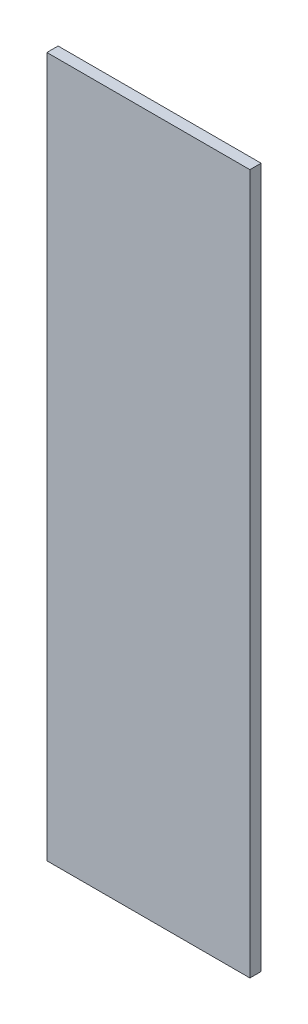
SolidWorks part; units mm, degrees
material "A-Glass Fiber"
ref_plane "Front Plane" through (0, 0, 0) normal (0, 0, 1) x (1, 0, 0)
ref_plane "Top Plane" through (0, 0, 0) normal (0, 1, 0) x (1, 0, 0)
ref_plane "Right Plane" through (0, 0, 0) normal (1, 0, 0) x (0, 0, -1)
sketch "Sketch1" plane through (0, 0, 0) normal (0, 0, 1) x (1, 0, 0)
  line L1 (0, 0) -> (29, 0)
  line L2 (0, 0) -> (0, 100)
  line L3 (0, 100) -> (29, 100)
  line L4 (29, 0) -> (29, 100)
  dimension "D1" = 29
  dimension "D2" = 100
extrude "Boss-Extrude1" add sketch "Sketch1" along normal blind 1.6
